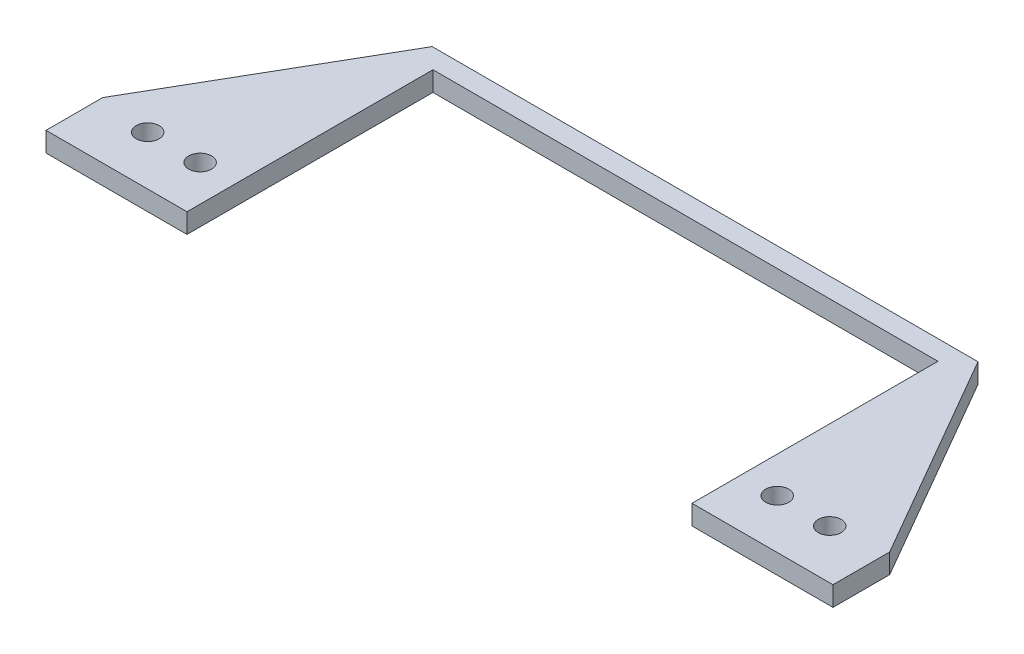
SolidWorks part; units mm, degrees
material "ABS"
ref_plane "Front Plane" through (0, 0, 0) normal (0, 0, 1) x (1, 0, 0)
ref_plane "Top Plane" through (0, 0, 0) normal (0, 1, 0) x (1, 0, 0)
ref_plane "Right Plane" through (0, 0, 0) normal (1, 0, 0) x (0, 0, -1)
sketch "Sketch1" plane through (0, 0, 0) normal (0, 1, 0) x (1, 0, 0)
  line L0 (-41.6114, 23.0814) -> (41.6114, 23.0814)
  line L1 (41.6114, 23.0814) -> (60, -8.7686)
  line L2 (60, -8.7686) -> (60, -17.4186)
  line L3 (60, -17.4186) -> (38.5, -17.4186)
  line L4 (38.5, -17.4186) -> (38.5, 20.0814)
  line L5 (0, 20.0814) -> (0, -17.4186) construction
  line L6 (38.5, 20.0814) -> (-38.5, 20.0814)
  line L8 (-41.6114, 23.0814) -> (-60, -8.7686)
  line L9 (-60, -8.7686) -> (-60, -17.4186)
  line L10 (-60, -17.4186) -> (-38.5, -17.4186)
  line L11 (-38.5, -17.4186) -> (-38.5, 20.0814)
  point P0 (60, -13.0936)
  dimension "D1" = 37.5
  dimension "D2" = 21.5
  dimension "D3" = 8.65
  dimension "D4" = 60
  dimension "D5" = 3
  dimension "D6" = 30
extrude "Boss-Extrude1" add sketch "Sketch1" along normal blind 3
sketch "Sketch2" plane through (0, 3, 0) normal (0, 1, 0) x (1, 0, 0)
  line L0 (60, -9.9186) -> (-60, -9.9186) construction
  line L1 (60, -17.4186) -> (60, -8.7686) construction
  line L2 (-60, -8.7686) -> (-60, -17.4186) construction
  line L3 (38.5, -17.4186) -> (60, -17.4186) construction
  line L4 (0, 23.0814) -> (0, -9.9186) construction
  line L5 (41.6114, 23.0814) -> (-41.6114, 23.0814) construction
  circle A0 centre (52, -9.9186) radius 1.75
  circle A1 centre (44, -9.9186) radius 1.75
  circle A4 centre (-52, -9.9186) radius 1.75
  circle A5 centre (-44, -9.9186) radius 1.75
  dimension "D3" = 3.5
  dimension "D1" = 7.5
  dimension "D2" = 8
  dimension "D4" = 8
extrude "Cut-Extrude1" cut sketch "Sketch2" against normal through all
